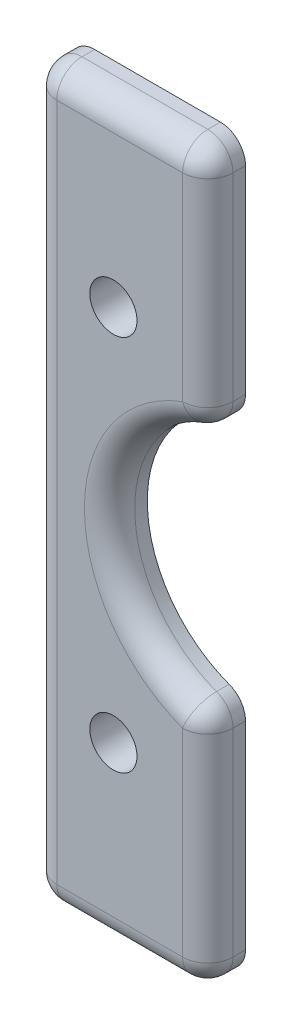
SolidWorks part; units mm, degrees
ref_plane "Front" through (0, 0, 0) normal (0, 0, 1) x (1, 0, 0)
ref_plane "Top" through (0, 0, 0) normal (0, 1, 0) x (1, 0, 0)
ref_plane "Right" through (0, 0, 0) normal (1, 0, 0) x (0, 0, -1)
sketch "Sketch1" plane through (0, 0, 0) normal (0, 0, 1) x (1, 0, 0)
  line L0 (-40.4977, -59.0134) -> (-18.9977, -59.0134) construction
  line L1 (-20.9977, -1.0134) -> (-30.9976, -1.0134)
  line L2 (-18.9977, -3.0134) -> (-18.9977, -18.7651)
  line L3 (-20.9977, -59.0134) -> (-30.9976, -59.0134)
  line L4 (-32.9976, -3.0134) -> (-32.9976, -57.0134)
  line L5 (-32.9976, -60.0134) -> (-32.9976, -0.0134) construction
  line L6 (-18.9977, -41.252) -> (-18.9977, -57.0134)
  circle A0 centre (-26.5018, -7.5086) radius 4.1 construction
  circle A1 centre (-26.5018, -52.5086) radius 4.1 construction
  circle A2 centre (-26.5018, -52.5086) radius 4.1 construction
  circle A3 centre (-26.5018, -7.5086) radius 4.1 construction
  arc A4 (-20.2988, -20.639) -> (-20.2988, -39.3781) centre (-16.8042, -30.0086) ccw
  arc A6 (-20.03, -20.5431) -> (-20.03, -39.474) centre (-16.8042, -30.0086) ccw construction
  arc A7 (-20.9977, -59.0134) -> (-18.9977, -57.0134) centre (-20.9977, -57.0134) ccw
  arc A8 (-30.9976, -59.0134) -> (-32.9976, -57.0134) centre (-30.9976, -57.0134) cw
  arc A9 (-32.9976, -3.0134) -> (-30.9976, -1.0134) centre (-30.9976, -3.0134) cw
  arc A10 (-20.9977, -1.0134) -> (-18.9977, -3.0134) centre (-20.9977, -3.0134) cw
  arc A11 (-18.9977, -41.252) -> (-20.2988, -39.3781) centre (-20.9977, -41.252) ccw
  arc A12 (-20.2988, -20.639) -> (-18.9977, -18.7651) centre (-20.9977, -18.7651) ccw
  circle A13 centre (-26.5018, -15.0086) radius 1.875
  circle A14 centre (-26.5018, -45.0086) radius 1.875
  circle A15 centre (-26.5018, -15.0086) radius 1.4 construction
  circle A16 centre (-26.5018, -45.0086) radius 1.4 construction
  point P27 (-32.9976, -59.0134)
  point P32 (-18.9977, -1.0134)
  dimension "D1" = 2
  dimension "D2" = 3.75
extrude "Boss-Extrude1" add sketch "Sketch1" along normal blind 3
fillet "Fillet1" radius 2 12 edges at (-19.3549, -19.9058, 3) (-26.8042, -30.0086, 3) (-19.3549, -40.1113, 3) (-18.9977, -49.1327, 3) (-19.5835, -58.4277, 3) (-25.9977, -59.0134, 3) (-32.4118, -58.4277, 3) (-32.9976, -30.0134, 3) (-32.4118, -1.5992, 3) (-25.9977, -1.0134, 3) (-19.5835, -1.5992, 3) (-18.9977, -10.8893, 3)
sketch "Sketch2" plane through (0, 0, 3) normal (0, 0, 1) x (1, 0, 0)
  line L0 (-26.5018, -7.5086) -> (-26.5018, -52.5086) construction
  circle A0 centre (-26.5018, -7.5086) radius 3.75
  circle A1 centre (-26.5018, -52.5086) radius 3.75
  circle A2 centre (-26.5018, -7.5086) radius 4.1 construction
  circle A3 centre (-26.5018, -52.5086) radius 4.1 construction
  dimension "D1" = 7.5
extrude "Boss-Extrude2" add sketch "Sketch2" against normal blind 4
